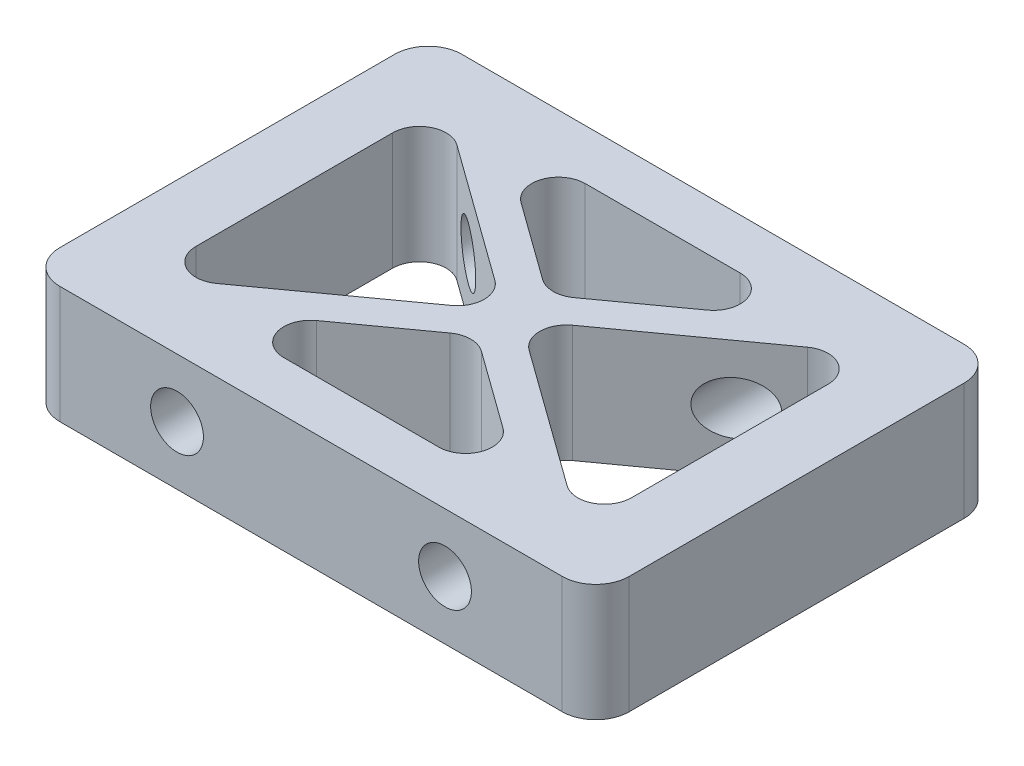
SolidWorks part; units mm, degrees
material "ABS"
ref_plane "Front Plane" through (0, 0, 0) normal (0, 0, 1) x (1, 0, 0)
ref_plane "Top Plane" through (0, 0, 0) normal (0, 1, 0) x (1, 0, 0)
ref_plane "Right Plane" through (0, 0, 0) normal (1, 0, 0) x (0, 0, -1)
sketch "Sketch1" plane through (0, 0, 0) normal (0, 0, 1) x (1, 0, 0)
  line L1 (0, 0) -> (53.975, 0)
  line L2 (0, 0) -> (0, -11.1125)
  line L3 (0, -11.1125) -> (53.975, -11.1125)
  line L4 (53.975, 0) -> (53.975, -11.1125)
  dimension "D1" = 53.975
  dimension "D2" = 11.1125
extrude "Boss-Extrude1" add sketch "Sketch1" along normal blind 38.1 contours L2 L1 L4 L3
fillet "Fillet1" radius 3.175 4 edges at (53.975, -5.5562, 38.1) (53.975, -5.5562, 0) (0, -5.5562, 38.1) (0, -5.5562, 0)
sketch "Sketch2" plane through (0, 0, 0) normal (0, 1, 0) x (1, 0, 0)
  line L0 (6.35, -9.7263) -> (6.35, -28.3737)
  line L1 (10.3759, -30.4338) -> (23.3027, -21.1101)
  line L2 (23.3027, -16.9899) -> (10.3759, -7.6662)
  line L3 (18.1553, -9.3626) -> (25.5016, -14.6613)
  line L4 (28.4734, -14.6613) -> (35.8197, -9.3626)
  line L5 (34.3339, -4.7625) -> (19.6411, -4.7625)
  line L6 (18.1553, -28.7374) -> (25.5016, -23.4387)
  line L7 (28.4734, -23.4387) -> (35.8197, -28.7374)
  line L8 (34.3339, -33.3375) -> (19.6411, -33.3375)
  line L9 (47.625, -9.7263) -> (47.625, -28.3737)
  line L10 (43.5991, -30.4338) -> (30.6723, -21.1101)
  line L11 (30.6723, -16.9899) -> (43.5991, -7.6662)
  line L12 (3.175, 0) -> (50.8, 0) construction
  line L13 (0, -34.925) -> (0, -3.175) construction
  line L14 (53.975, -34.925) -> (53.975, -3.175) construction
  line L15 (3.175, -38.1) -> (50.8, -38.1) construction
  line L16 (26.9875, -12.6012) -> (26.9875, -25.4988) construction
  line L17 (32.1581, -19.05) -> (21.8169, -19.05) construction
  arc A0 (34.3339, -4.7625) -> (35.8197, -9.3626) centre (34.3339, -7.3025) cw
  arc A1 (28.4734, -14.6613) -> (25.5016, -14.6613) centre (26.9875, -12.6012) cw
  arc A2 (19.6411, -4.7625) -> (18.1553, -9.3626) centre (19.6411, -7.3025) ccw
  arc A3 (28.4734, -23.4387) -> (25.5016, -23.4387) centre (26.9875, -25.4988) ccw
  arc A4 (34.3339, -33.3375) -> (35.8197, -28.7374) centre (34.3339, -30.7975) ccw
  arc A5 (18.1553, -28.7374) -> (19.6411, -33.3375) centre (19.6411, -30.7975) ccw
  arc A6 (23.3027, -16.9899) -> (23.3027, -21.1101) centre (21.8169, -19.05) cw
  arc A7 (10.3759, -30.4338) -> (6.35, -28.3737) centre (8.89, -28.3737) cw
  arc A8 (10.3759, -7.6662) -> (6.35, -9.7263) centre (8.89, -9.7263) ccw
  arc A9 (43.5991, -30.4338) -> (47.625, -28.3737) centre (45.085, -28.3737) ccw
  arc A10 (30.6723, -16.9899) -> (30.6723, -21.1101) centre (32.1581, -19.05) ccw
  arc A11 (43.5991, -7.6662) -> (47.625, -9.7263) centre (45.085, -9.7263) cw
  point P3 (26.9875, -19.05)
  point P11 (26.9875, -4.7625)
  point P13 (6.35, -19.05)
  point P14 (47.625, -19.05)
  point P15 (26.9875, -33.3375)
  point P17 (0, -19.05)
  point P27 (26.9875, 0)
  point P42 (42.1975, -33.3375)
  point P45 (11.7775, -33.3375)
  point P51 (6.35, -33.3375)
  point P54 (6.35, -4.7625)
  point P57 (47.625, -33.3375)
  point P63 (47.625, -4.7625)
  dimension "D8" = 2.54
  dimension "D9" = 2.54
  dimension "D11" = 2.54
  dimension "D12" = 2.54
  dimension "D1" = 28.575
  dimension "D2" = 6.35
  dimension "D3" = 6.35
  dimension "D4" = 4.7625
  dimension "D5" = 4.7625
  dimension "D6" = 54.198
  dimension "D7" = 3.175
  dimension "D10" = 28.575
extrude "Cut-Extrude1" cut sketch "Sketch2" against normal through all
sketch "Sketch3" plane through (0, 0, 38.1) normal (0, 0, 1) x (1, 0, 0)
  line L0 (14.2875, -5.5562) -> (39.6875, -5.5562) construction
  line L1 (3.175, 0) -> (3.175, -11.1125) construction
  line L2 (3.175, -11.1125) -> (50.8, -11.1125) construction
  circle A0 centre (14.2875, -5.5562) radius 2.5019
  circle A1 centre (39.6875, -5.5562) radius 2.5019
  point P0 (14.2875, -5.5562)
  point P1 (39.6875, -5.5562)
  point P4 (3.175, -5.5562)
  point P8 (26.9875, -11.1125)
  point P9 (26.9875, -5.5562)
  dimension "D2" = 5.0038
  dimension "D1" = 25.4
extrude "Cut-Extrude2" cut sketch "Sketch3" against normal blind 38.1
fillet "Fillet2" [suppressed] radius 0.254
